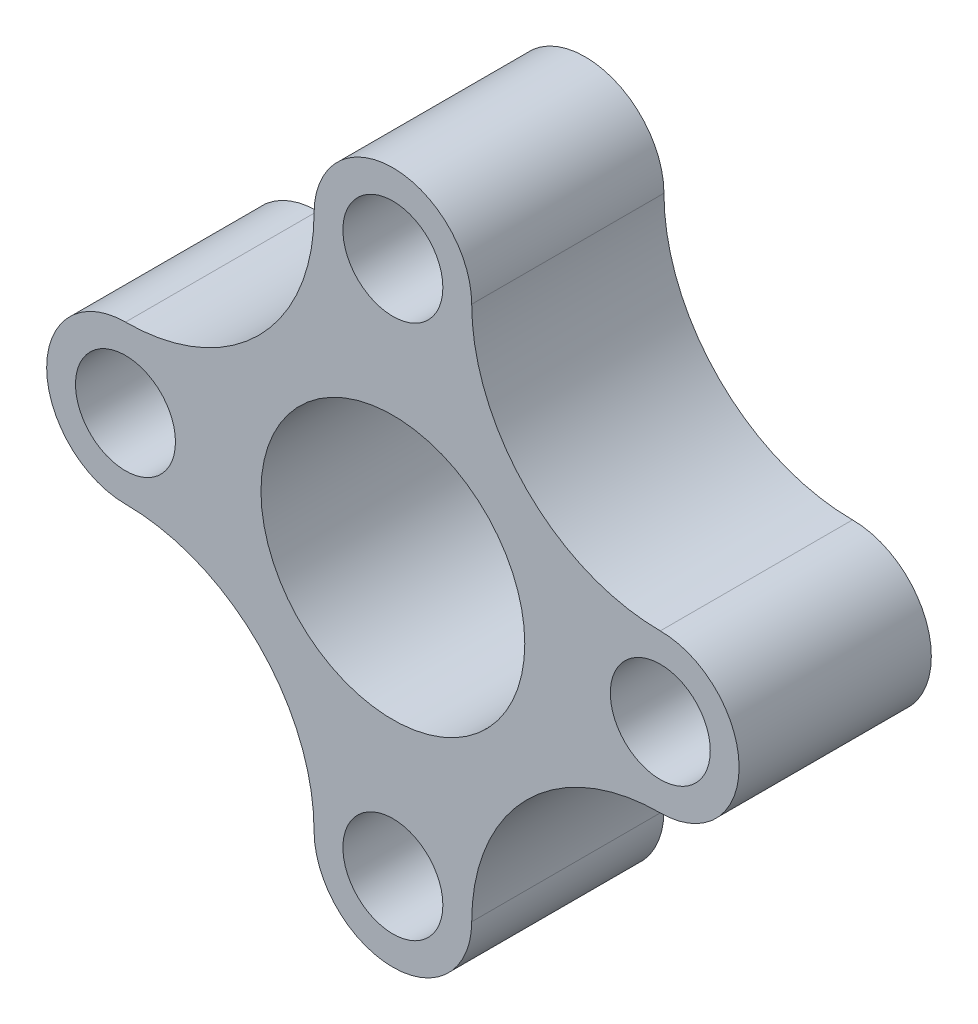
SolidWorks part; units mm, degrees
ref_plane "xy" through (0, 0, 0) normal (0, 0, 1) x (1, 0, 0)
ref_plane "xz" through (0, 0, 0) normal (0, 1, 0) x (1, 0, 0)
ref_plane "yz" through (0, 0, 0) normal (1, 0, 0) x (0, 0, -1)
sketch "Skizze1" plane through (0, 0, 0) normal (0, 0, 1) x (1, 0, 0)
  line L0 (0, 18.0102) -> (0, 0)
  line L1 (0, 0) -> (7.9102, 0) construction
  line L2 (0, 0) -> (0, 7.9102) construction
  line L3 (0, 7.9102) -> (7.9102, 7.9102) construction
  line L4 (7.9102, 0) -> (7.9102, 7.9102) construction
  line L5 (0, 0) -> (18.0102, 0)
  line L6 (5.0888, 10.7315) -> (10.7315, 5.0888) construction
  circle A0 centre (13.9102, 0) radius 6 construction
  circle A1 centre (0, 13.9102) radius 6 construction
  circle A2 centre (0, 13.9102) radius 2.6 construction
  circle A3 centre (13.9102, 0) radius 2.6 construction
  arc A4 (0, 18.0102) -> (4.1, 13.9102) centre (0, 13.9102) cw
  arc A5 (18.0102, 0) -> (13.9102, 4.1) centre (13.9102, 0) ccw
  arc A6 (4.1, 13.9102) -> (13.9102, 4.1) centre (13.9102, 13.9102) ccw
  dimension "D2" = 12
  dimension "D3" = 5.2
  dimension "D4" = 1.5
  dimension "D1" = 7.98
extrude "Aufsatz-Linear austragen1" add sketch "Skizze1" along normal blind 10
mirror "Spiegeln1" about plane through (0, 0, 0) normal (0, 1, 0) of bodies 101
mirror "Spiegeln2" about plane through (0, 0, 0) normal (1, 0, 0) of bodies 102
sketch "Skizze2" plane through (0, 0, 0) normal (0, 0, 1) x (1, 0, 0)
  line L0 (-13.9102, 0) -> (0, 13.9102) construction
  line L1 (-13.9102, 0) -> (0, -13.9102) construction
  line L2 (0, 13.9102) -> (13.9102, 0) construction
  line L3 (0, -13.9102) -> (13.9102, 0) construction
  line L4 (-13.9102, 0) -> (13.9102, 0) construction
  line L5 (0, 13.9102) -> (0, -13.9102) construction
  circle A0 centre (0, 13.9102) radius 2.6
  circle A1 centre (13.9102, 0) radius 2.6
  circle A2 centre (0, -13.9102) radius 2.6
  circle A3 centre (-13.9102, 0) radius 2.6
  circle A4 centre (0, 13.9102) radius 2.6 construction
  point P1 (0, 0)
extrude "Schnitt-Linear austragen2" cut sketch "Skizze2" along normal blind 10
sketch "Skizze3" plane through (0, 0, 0) normal (0, 0, 1) x (1, 0, 0)
  line L0 (0, 18.0102) -> (0, 0) construction
  line L1 (-6.9733, 6.9733) -> (-4.852, 4.852) construction
  circle A0 centre (0, 0) radius 6.8618
  circle A1 centre (0, 13.9102) radius 2.6 construction
  arc A2 (-13.9102, 4.1) -> (-4.1, 13.9102) centre (-13.9102, 13.9102) ccw construction
  point P3 (0, 6.8618)
  point P4 (0, 11.3102)
  point P5 (-6.9733, 6.9733)
  dimension "D1" = 3
extrude "Schnitt-Linear austragen4" cut sketch "Skizze3" along normal blind 10
